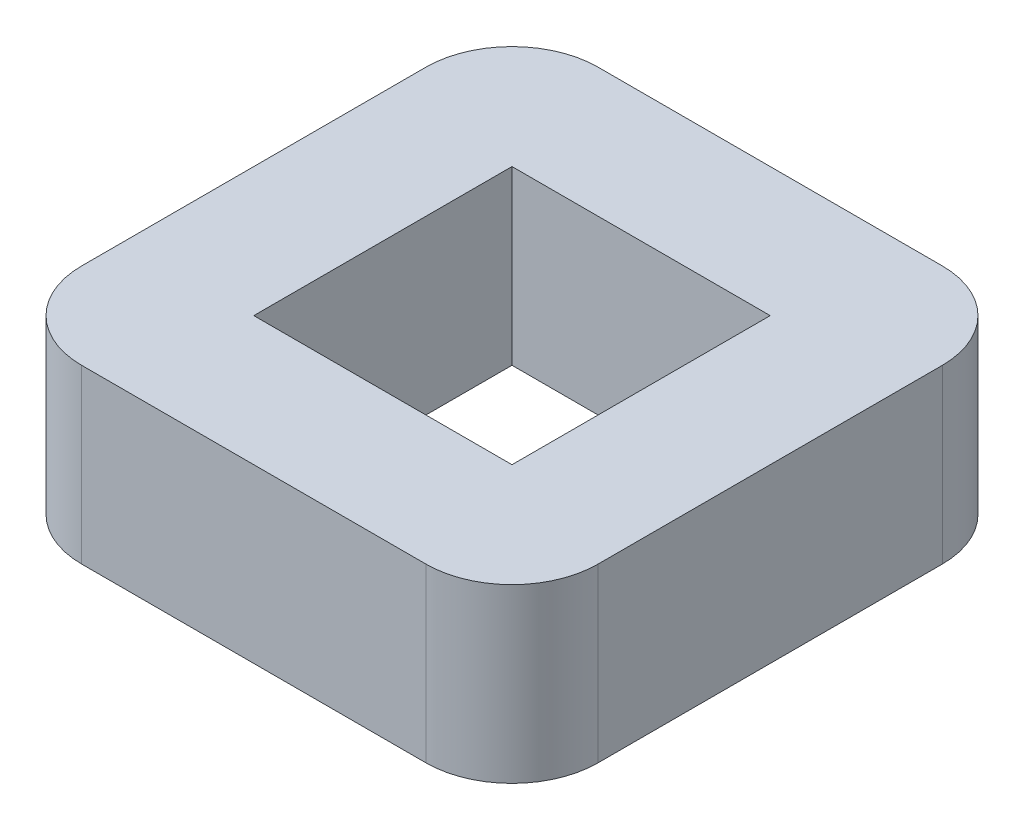
SolidWorks part; units mm, degrees
material "Copper"
ref_plane "Front Plane" through (0, 0, 0) normal (0, 0, 1) x (1, 0, 0)
ref_plane "Top Plane" through (0, 0, 0) normal (0, 1, 0) x (1, 0, 0)
ref_plane "Right Plane" through (0, 0, 0) normal (1, 0, 0) x (0, 0, -1)
sketch "Sketch1" plane through (0, 0, 0) normal (0, 1, 0) x (1, 0, 0)
  line L1 (-20, 30) -> (20, 30)
  line L2 (-30, 20) -> (-30, -20)
  line L3 (-20, -30) -> (20, -30)
  line L4 (30, 20) -> (30, -20)
  line L5 (-30, 30) -> (30, -30) construction
  line L6 (-30, -30) -> (30, 30) construction
  line L7 (-15, 15) -> (15, 15)
  line L8 (-15, 15) -> (-15, -15)
  line L9 (-15, -15) -> (15, -15)
  line L10 (15, 15) -> (15, -15)
  line L11 (-15, 15) -> (15, -15) construction
  line L12 (-15, -15) -> (15, 15) construction
  arc A0 (-20, -30) -> (-30, -20) centre (-20, -20) cw
  arc A1 (30, -20) -> (20, -30) centre (20, -20) cw
  arc A2 (20, 30) -> (30, 20) centre (20, 20) cw
  arc A3 (-20, 30) -> (-30, 20) centre (-20, 20) ccw
  point P0 (0, 0)
  point P6 (0, 0)
  point P11 (0, 0)
  dimension "D5" = 10
  dimension "D1" = 60
  dimension "D2" = 60
  dimension "D3" = 30
  dimension "D4" = 30
extrude "Boss-Extrude1" add sketch "Sketch1" along normal mid plane 20
